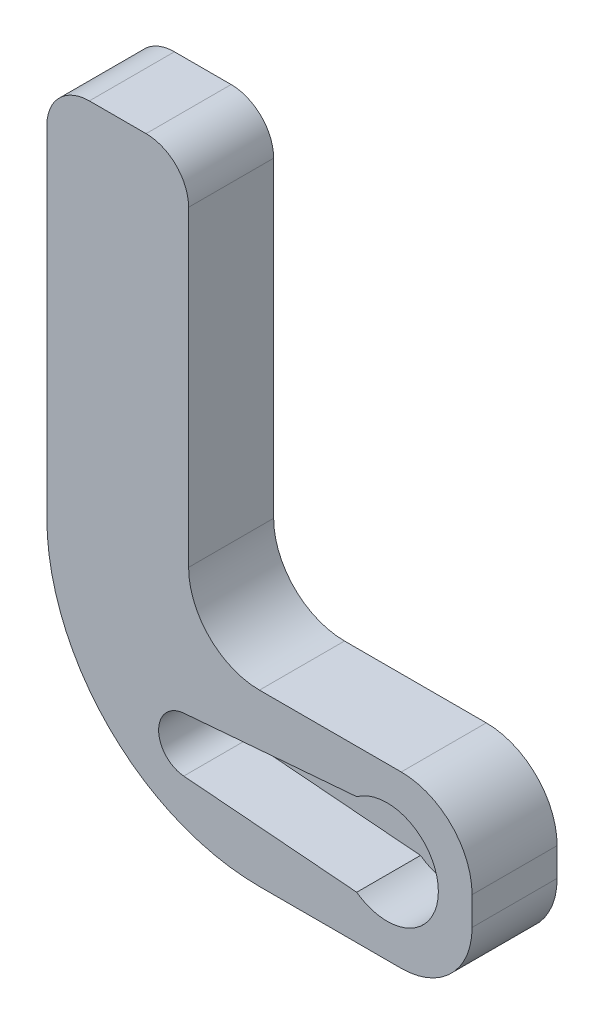
SolidWorks part; units mm, degrees
ref_plane "Front Plane" through (0, 0, 0) normal (0, 0, 1) x (1, 0, 0)
ref_plane "Top Plane" through (0, 0, 0) normal (0, 1, 0) x (1, 0, 0)
ref_plane "Right Plane" through (0, 0, 0) normal (1, 0, 0) x (0, 0, -1)
sketch "Sketch1" plane through (0, 0, 0) normal (0, 0, 1) x (1, 0, 0)
  line L0 (-16.116, 0) -> (3.62, 0) construction
  line L1 (-14.3431, 1.9236) -> (-2.1396, 2.92)
  line L3 (-14.3431, -1.9236) -> (-2.1396, -2.92)
  arc A0 (-14.3431, 1.9236) -> (-14.3431, -1.9236) centre (-14.186, 0) ccw
  arc A1 (-2.1396, -2.92) -> (-2.1396, 2.92) centre (0, 0) ccw
  point P5 (3.62, 0)
  point P7 (0, 0)
  point P8 (-14.6696, -1.1571)
  point P9 (-15.38, 0)
  point P13 (-15.3457, -1.1419)
  point P14 (0, 0)
  point P15 (0, 0)
  dimension "D3" = 5.84
  dimension "D1" = 1.93
  dimension "D2" = 3.62
  dimension "D4" = 19.736
sketch "Sketch2" plane through (0, 0, 0) normal (0, 0, 1) x (1, 0, 0)
  line L0 (6, 0) -> (-24, 0) construction
  line L1 (-14, 6) -> (6, 6)
  line L2 (-24, 6) -> (-24, -6)
  line L3 (-24, -6) -> (6, -6)
  line L4 (6, 6) -> (6, -6)
  line L5 (-16.116, 0) -> (3.62, 0) construction
  line L8 (-14, 6) -> (-14, 36)
  line L9 (-14, 36) -> (-24, 36)
  line L10 (-24, 6) -> (-24, 36)
  dimension "D1" = 12
  dimension "D2" = 30
  dimension "D3" = 6
  dimension "D4" = 10
  dimension "D5" = 30
extrude "Boss-Extrude1" add sketch "Sketch2" against normal blind 6 contours L2 L3 L4 L1 L8 L9 L10
fillet "Fillet1" radius 5 1 edges at (-14, 6, -3)
fillet "Fillet2" radius 15 1 edges at (-24, -6, -3)
fillet "Fillet3" radius 5 1 edges at (6, 6, -3)
fillet "Fillet4" radius 5 1 edges at (6, -6, -3)
fillet "Fillet5" radius 3 1 edges at (-14, 36, -3)
fillet "Fillet6" radius 3 1 edges at (-24, 36, -3)
extrude "Cut-Extrude1" cut sketch "Sketch1" against normal blind 4.5
sketch "Sketch3" plane through (0, 0, -4.5) normal (0, 0, 1) x (1, 0, 0)
  circle A0 centre (0, 0) radius 1.5
  dimension "D1" = 3
extrude "Cut-Extrude2" cut sketch "Sketch3" against normal blind 5
